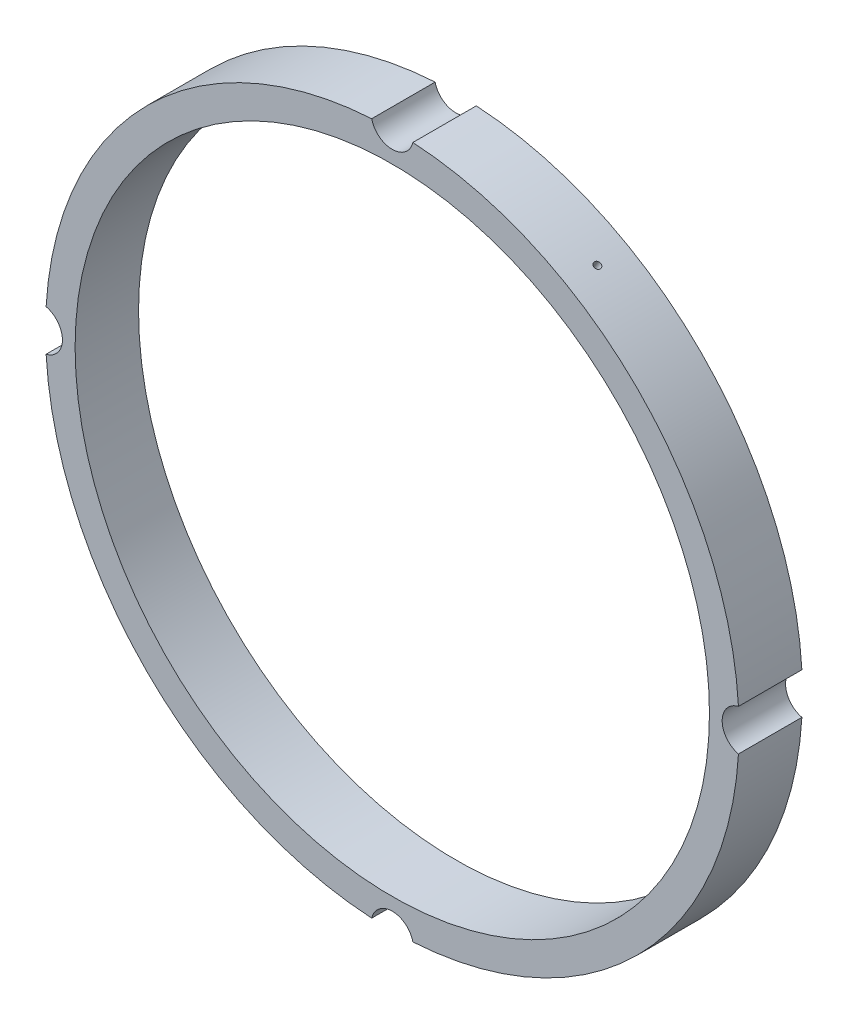
SolidWorks part; units mm, degrees
ref_plane "Front Plane" through (0, 0, 0) normal (0, 0, 1) x (1, 0, 0)
ref_plane "Top Plane" through (0, 0, 0) normal (0, 1, 0) x (1, 0, 0)
ref_plane "Right Plane" through (0, 0, 0) normal (1, 0, 0) x (0, 0, -1)
sketch "Sketch1" plane through (0, 0, 0) normal (0, 0, 1) x (1, 0, 0)
  circle A0 centre (0, 0) radius 75
  circle A1 centre (0, 0) radius 82
extrude "Boss-Extrude1" add sketch "Sketch1" along normal blind 15
sketch "Sketch2" plane through (0, 0, 15) normal (0, 0, 1) x (1, 0, 0)
  circle A0 centre (0, 83) radius 5
extrude "Cut-Extrude1" cut sketch "Sketch2" against normal through all
pattern_circular "CirPattern1" count 4 every 90 about axis through (0, 0, 0) along (0, 0, 1) of "Cut-Extrude1"
hole_wizard "M2x0.4 Tapped Hole1" positions "3DSketch1" profile "Sketch3" tap size "M2x0.4" standard "ANSI Metric"
sketch3d "3DSketch1"
  point P0 (41, 71.0141, 7.5)
sketch "Sketch3" plane through (41, 71.0141, 7.5) normal (0, 0, 1) x (-0.866, 0.5, 0)
  line L0 (0, 0) -> (0, 10.4807)
  line L1 (0, 10.4807) -> (0.8, 10)
  line L2 (0.8, 10) -> (0.8, 0)
  line L5 (0.8, 0) -> (0, 0)
  line L10 (0, 10.4807) -> (-0.8, 10) construction
  line L11 (0, -6.35) -> (0, 107.95) construction
  dimension "Tap Drill Dia." = 1.6
  dimension "Tap Drill Depth" = 10
  dimension "Drill Angle" = 118
cosmetic thread "Hole Thread1" parameters "D1"=4, "D2"=2
